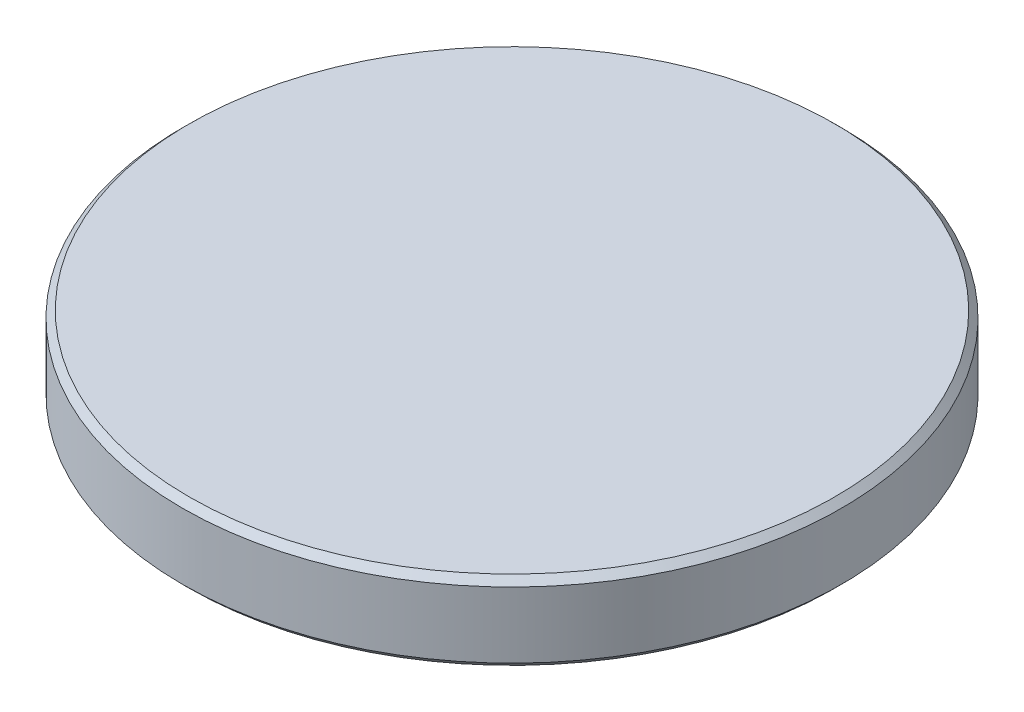
SolidWorks part; units mm, degrees
ref_plane "Front Plane" through (0, 0, 0) normal (0, 0, 1) x (1, 0, 0)
ref_plane "Top Plane" through (0, 0, 0) normal (0, 1, 0) x (1, 0, 0)
ref_plane "Right Plane" through (0, 0, 0) normal (1, 0, 0) x (0, 0, -1)
sketch "Sketch1" plane through (0, 0, 0) normal (0, 1, 0) x (1, 0, 0)
  circle A0 centre (0, 0) radius 12.5
  dimension "D1" = 25
extrude "Boss-Extrude1" add sketch "Sketch1" along normal blind 3
chamfer "Chamfer1" distance 0.25 angle 45 2 edges at (0, 0, 12.5) (0, 3, 12.5)
sketch "Esboço1" plane through (0, 3, 0) normal (0, 1, 0) x (1, 0, 0)
  circle A0 centre (0, 0) radius 0.6213
extrude "Corte-extrusão1" [suppressed] cut sketch "Esboço1" against normal blind 10
sketch "Sketch2" plane through (0, 3, 0) normal (0, 1, 0) x (1, 0, 0)
  point P0 (0, 0)
